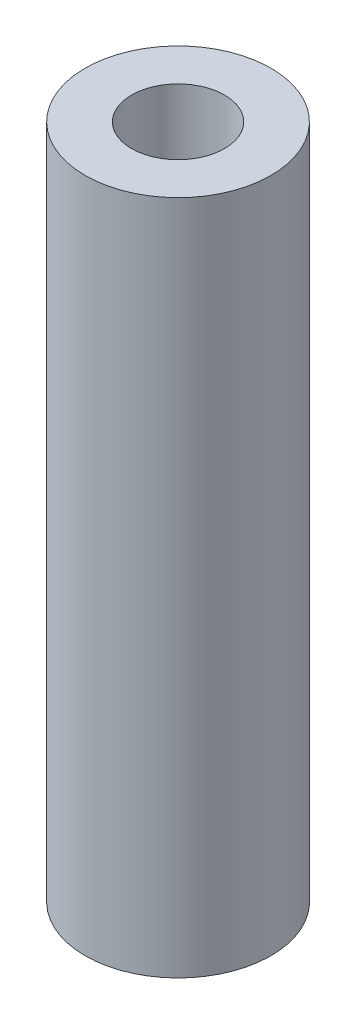
SolidWorks part; units mm, degrees
ref_plane "Front Plane" through (0, 0, 0) normal (0, 0, 1) x (1, 0, 0)
ref_plane "Top Plane" through (0, 0, 0) normal (0, 1, 0) x (1, 0, 0)
ref_plane "Right Plane" through (0, 0, 0) normal (1, 0, 0) x (0, 0, -1)
sketch "Sketch1" plane through (0, 0, 0) normal (0, 1, 0) x (1, 0, 0)
  circle A0 centre (0, 0) radius 11
  circle A1 centre (0, 0) radius 5.5
  dimension "D1" = 11
  dimension "D2" = 22
extrude "Boss-Extrude1" add sketch "Sketch1" along normal mid plane 80
